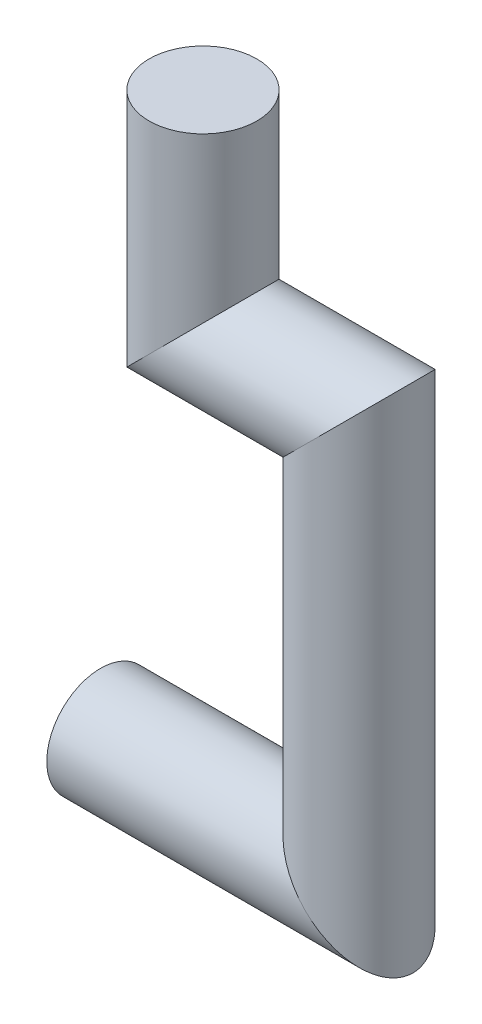
SolidWorks part; units mm, degrees
ref_plane "Front Plane" through (0, 0, 0) normal (0, 0, 1) x (1, 0, 0)
ref_plane "Top Plane" through (0, 0, 0) normal (0, 1, 0) x (1, 0, 0)
ref_plane "Right Plane" through (0, 0, 0) normal (1, 0, 0) x (0, 0, -1)
sketch "Sketch1" plane through (0, 0, 0) normal (0, 0, 1) x (1, 0, 0)
  line L0 (38, 100) -> (38, 25)
  line L1 (0, -55) -> (0, 55) construction
  line L2 (38, 25) -> (96, 25)
  line L4 (96, 25) -> (96, -125)
  line L5 (96, -125) -> (0, -125)
  point P5 (12.0505, 0)
sketch "Sketch2" plane through (0, 0, 0) normal (1, 0, 0) x (0, 0, -1)
  line L0 (0, 25) -> (0, -125) construction
  circle A0 centre (0, -125) radius 20
sweep "Sweep3" add profiles "Sketch2" path "Sketch1"
